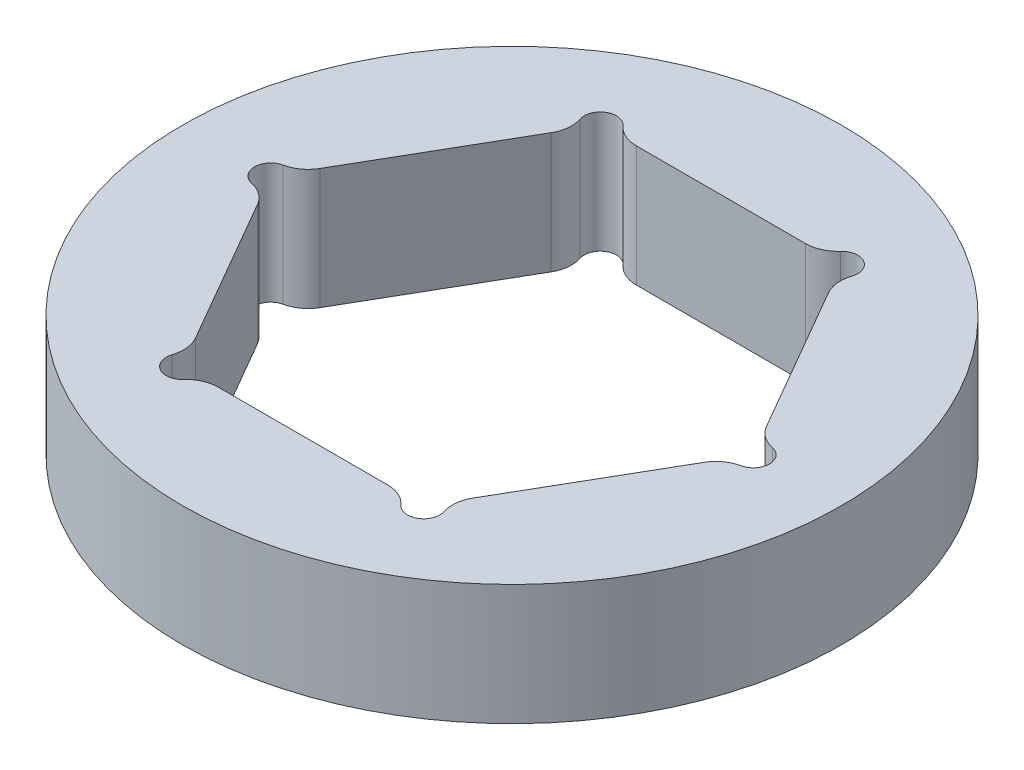
SolidWorks part; units mm, degrees
material "ABS"
ref_plane "Alzado" through (0, 0, 0) normal (0, 0, 1) x (1, 0, 0)
ref_plane "Planta" through (0, 0, 0) normal (0, 1, 0) x (1, 0, 0)
ref_plane "Vista lateral" through (0, 0, 0) normal (1, 0, 0) x (0, 0, -1)
sketch "Croquis1" plane through (0, 0, 0) normal (0, 1, 0) x (1, 0, 0)
  line L1 (1.7247, -2.2127) -> (2.7786, -0.3873)
  line L2 (2.7786, 0.3873) -> (1.7247, 2.2127)
  line L3 (1.0539, 2.6) -> (-1.0539, 2.6)
  line L4 (-1.7247, 2.2127) -> (-2.7786, 0.3873)
  line L5 (-2.7786, -0.3873) -> (-1.7247, -2.2127)
  line L6 (-1.0539, -2.6) -> (1.0539, -2.6)
  circle A0 centre (0, 0) radius 4.1
  circle A1 centre (0, 0) radius 2.6 construction
  arc A2 (-1.352, 2.7333) -> (-1.6911, 2.5376) centre (-1.5011, 2.6) ccw
  arc A3 (-1.352, 2.7333) -> (-1.0539, 2.6) centre (-1.0539, 3) ccw
  arc A4 (-1.7247, 2.2127) -> (-1.6911, 2.5376) centre (-2.0711, 2.4127) ccw
  arc A5 (1.6911, 2.5376) -> (1.352, 2.7333) centre (1.5011, 2.6) ccw
  arc A6 (1.6911, 2.5376) -> (1.7247, 2.2127) centre (2.0711, 2.4127) ccw
  arc A7 (1.0539, 2.6) -> (1.352, 2.7333) centre (1.0539, 3) ccw
  arc A8 (3.0432, -0.1958) -> (3.0432, 0.1958) centre (3.0022, 0) ccw
  arc A9 (3.0432, -0.1958) -> (2.7786, -0.3873) centre (3.125, -0.5873) ccw
  arc A10 (2.7786, 0.3873) -> (3.0432, 0.1958) centre (3.125, 0.5873) ccw
  arc A11 (1.352, -2.7333) -> (1.6911, -2.5376) centre (1.5011, -2.6) ccw
  arc A12 (1.352, -2.7333) -> (1.0539, -2.6) centre (1.0539, -3) ccw
  arc A13 (1.7247, -2.2127) -> (1.6911, -2.5376) centre (2.0711, -2.4127) ccw
  arc A14 (-1.6911, -2.5376) -> (-1.352, -2.7333) centre (-1.5011, -2.6) ccw
  arc A15 (-1.6911, -2.5376) -> (-1.7247, -2.2127) centre (-2.0711, -2.4127) ccw
  arc A16 (-1.0539, -2.6) -> (-1.352, -2.7333) centre (-1.0539, -3) ccw
  arc A17 (-3.0432, 0.1958) -> (-3.0432, -0.1958) centre (-3.0022, 0) ccw
  arc A18 (-3.0432, 0.1958) -> (-2.7786, 0.3873) centre (-3.125, 0.5873) ccw
  arc A19 (-2.7786, -0.3873) -> (-3.0432, -0.1958) centre (-3.125, -0.5873) ccw
  dimension "D2" = 8.2
  dimension "D3" = 0.4
  dimension "D4" = 0.4
  dimension "D1" = 5.2
  dimension "D5" = 6
extrude "Saliente-Extruir1" add sketch "Croquis1" along normal mid plane 1.5
